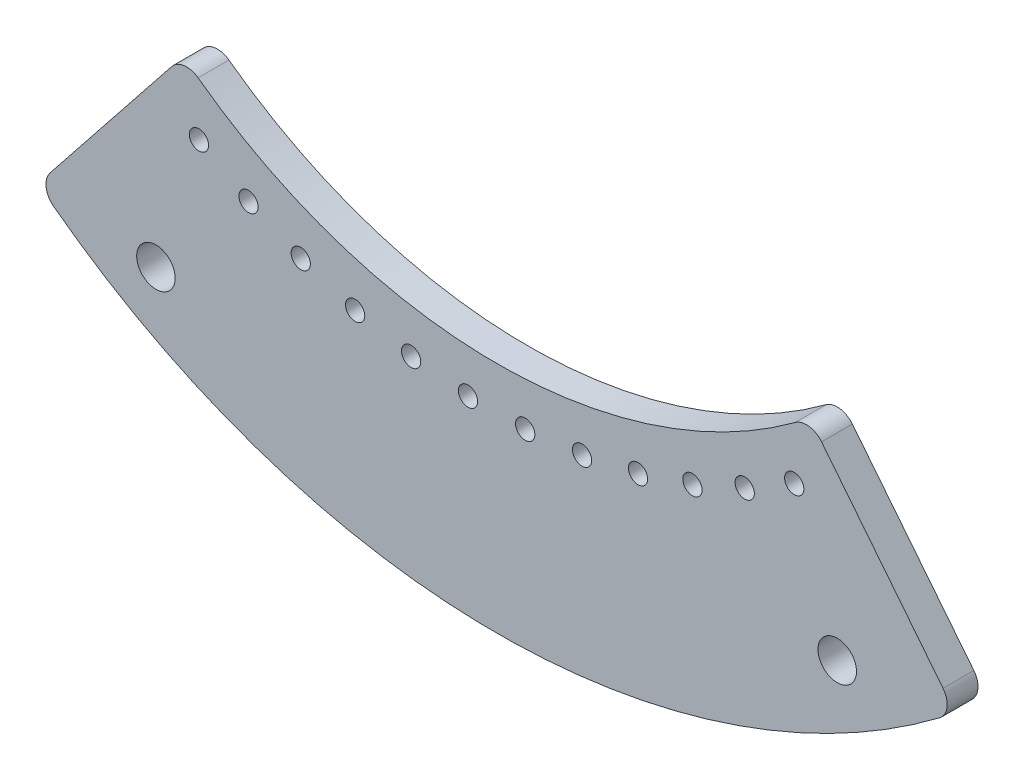
SolidWorks part; units mm, degrees
ref_plane "Front Plane" through (0, 0, 0) normal (0, 0, 1) x (1, 0, 0)
ref_plane "Top Plane" through (0, 0, 0) normal (0, 1, 0) x (1, 0, 0)
ref_plane "Right Plane" through (0, 0, 0) normal (1, 0, 0) x (0, 0, -1)
sketch "Sketch2" plane through (0, 0, 0) normal (0, 0, 1) x (1, 0, 0)
  line L0 (0, 0) -> (-15.4541, -23.7973) construction
  line L1 (-16.2632, -20.4456) -> (-23.8112, -29.9348)
  line L2 (0, 0) -> (0, -38.25) construction
  line L3 (16.2632, -20.4456) -> (23.8112, -29.9348)
  arc A0 (-16.2632, -20.4456) -> (16.2632, -20.4456) centre (0, 0) ccw
  circle A1 centre (0, 0) radius 32.5 construction
  arc A2 (-23.8112, -29.9348) -> (23.8112, -29.9348) centre (0, 0) ccw
  arc A7 (23.8112, -29.9348) -> (-23.8112, -29.9348) centre (0, 0) ccw construction
  arc A8 (16.2632, -20.4456) -> (-16.2632, -20.4456) centre (0, 0) ccw construction
  dimension "D2" = 65
  dimension "D3" = 76.5
  dimension "D4" = 52.25
  dimension "D5" = 33
  dimension "D1" = 38.5
extrude "Boss-Extrude2" add sketch "Sketch2" along normal blind 1.6
sketch "Sketch1" plane through (0, 0, 0) normal (0, 0, 1) x (1, 0, 0)
  line L0 (-205.5001, 267.7711) -> (279.6982, 267.7711) construction
  line L1 (0, 0) -> (0, -28.375) construction
  line L2 (0, 0) -> (-15.4541, -23.7973) construction
  line L3 (0, 0) -> (15.4541, -23.7973) construction
  circle A0 centre (0, 0) radius 38.25 construction
  circle A1 centre (0, 0) radius 32.5 construction
  circle A2 centre (0, 0) radius 28.375 construction
  circle A3 centre (-15.4541, -23.7973) radius 0.5
  circle A4 centre (-12.882, -25.2823) radius 0.5
  circle A5 centre (-10.1687, -26.4903) radius 0.5
  circle A6 centre (-7.344, -27.4081) radius 0.5
  circle A7 centre (-4.4388, -28.0257) radius 0.5
  circle A8 centre (-1.485, -28.3361) radius 0.5
  circle A9 centre (1.485, -28.3361) radius 0.5
  circle A10 centre (4.4388, -28.0257) radius 0.5
  circle A11 centre (7.344, -27.4081) radius 0.5
  circle A12 centre (10.1687, -26.4903) radius 0.5
  circle A13 centre (12.882, -25.2823) radius 0.5
  circle A14 centre (15.4541, -23.7973) radius 0.5
  point P12 (0, 0)
  point P35 (0, 0)
  dimension "D1" = 76.5
  dimension "D2" = 65
  dimension "D3" = 56.75
  dimension "D4" = 33
  dimension "D6" = 1
  dimension "D5" = 33
  dimension "D7" = 12
extrude "Cut-Extrude3" cut sketch "Sketch1" against normal through all from surface at 1.6 starting at face at (0, -28.6889, 1.6)
sketch "Sketch3" plane through (0, 0, 0) normal (0, 0, 1) x (1, 0, 0)
  line L0 (-17.6875, 30.6356) -> (0, 0) construction
  line L1 (0, 0) -> (0, 47.2588) construction
  line L2 (-17.6875, -30.6356) -> (0, 0) construction
  line L3 (0, 0) -> (-35.375, 0) construction
  circle A0 centre (0, 0) radius 35.375 construction
  circle A7 centre (-35.375, 0) radius 1.875 construction
  circle A8 centre (35.375, 0) radius 1.875 construction
  circle A9 centre (-17.6875, 30.6356) radius 1.875 construction
  circle A10 centre (17.6875, 30.6356) radius 1.875 construction
  circle A11 centre (17.6875, -30.6356) radius 1.875 construction
  circle A12 centre (-17.6875, -30.6356) radius 1.875 construction
  circle A13 centre (-17.6875, -30.6356) radius 1
  circle A14 centre (17.6875, -30.6356) radius 1
  point P9 (-37.25, 0)
  point P10 (-33.5, 0)
  point P11 (33.5, 0)
  point P12 (37.25, 0)
  dimension "D1" = 74.5
  dimension "D2" = 30
  dimension "D4" = 2
  dimension "D3" = 67
extrude "Cut-Extrude4" cut sketch "Sketch3" against normal blind 1.6 from surface at 1.6 starting at face at (-14.9541, -23.7973, 1.6)
fillet "Fillet1" radius 1 4 edges at (16.2632, -20.4456, 0.8) (23.8112, -29.9348, 0.8) (-23.8112, -29.9348, 0.8) (-16.2632, -20.4456, 0.8)
